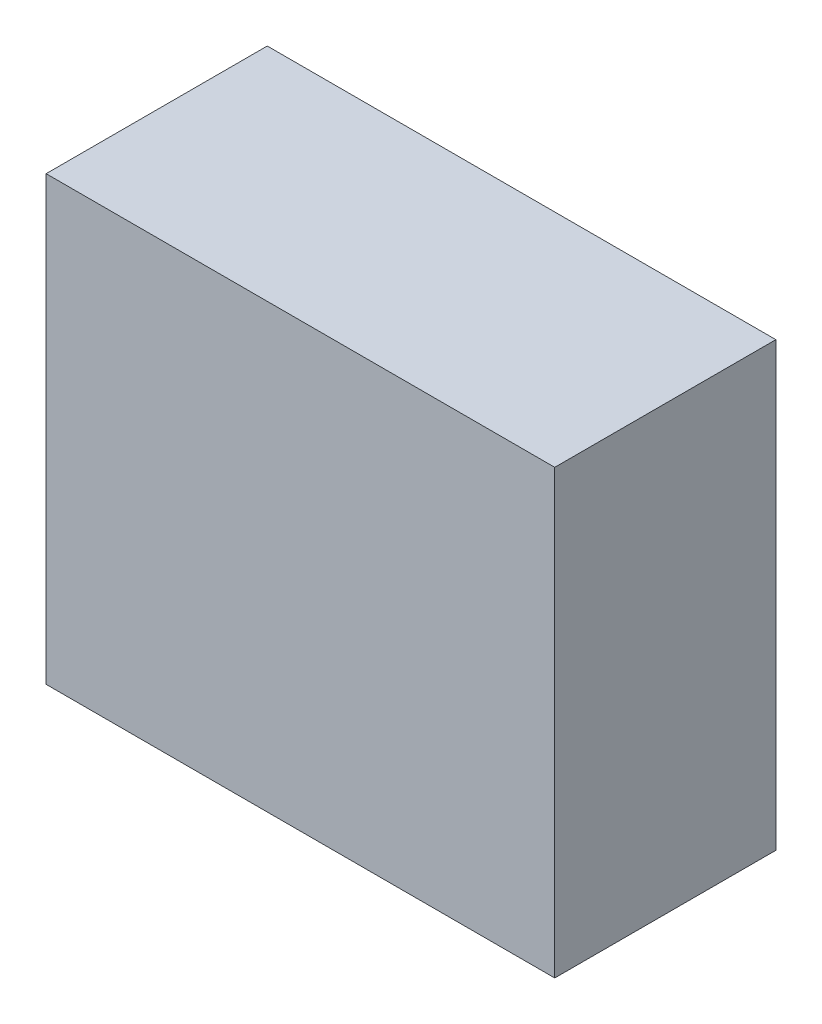
SolidWorks part; units mm, degrees
ref_plane "Front Plane" through (0, 0, 0) normal (0, 0, 1) x (1, 0, 0)
ref_plane "Top Plane" through (0, 0, 0) normal (0, 1, 0) x (1, 0, 0)
ref_plane "Right Plane" through (0, 0, 0) normal (1, 0, 0) x (0, 0, -1)
sketch "Sketch1" plane through (0, 0, 0) normal (0, 0, 1) x (1, 0, 0)
  line L1 (0, 0) -> (23, 0)
  line L2 (0, 0) -> (0, 20)
  line L3 (0, 20) -> (23, 20)
  line L4 (23, 0) -> (23, 20)
extrude "Boss-Extrude1" add sketch "Sketch1" against normal blind 10
